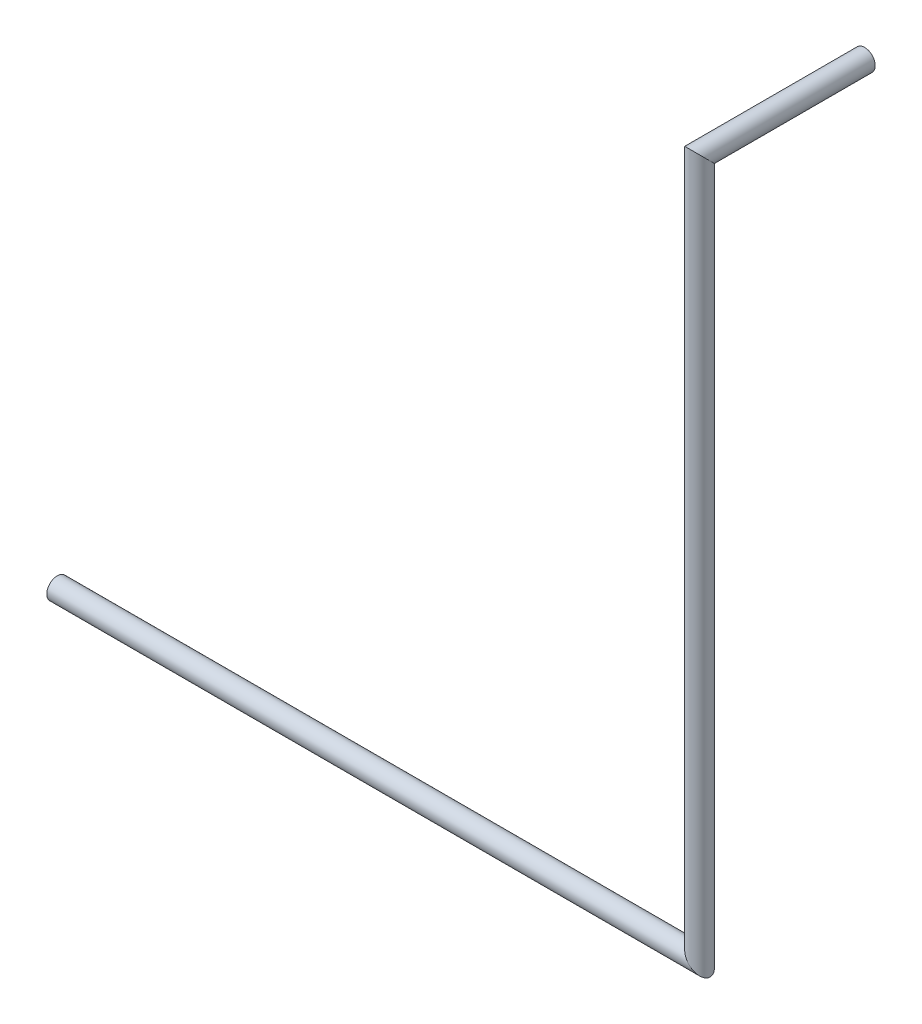
SolidWorks part; units mm, degrees
ref_plane "Plan de face" through (0, 0, 0) normal (0, 0, 1) x (1, 0, 0)
ref_plane "Plan de dessus" through (0, 0, 0) normal (0, 1, 0) x (1, 0, 0)
ref_plane "Plan de droite" through (0, 0, 0) normal (1, 0, 0) x (0, 0, -1)
sketch3d "Esquisse3D1"
  line L0 (0, 0, 0) -> (152.47, 0, 0)
  line L1 (152.47, 0, 0) -> (152.47, 165.26, 0)
  line L2 (152.47, 165.26, 0) -> (152.47, 165.26, -39.19)
  dimension "D1" = 152.47
  dimension "D2" = 165.26
  dimension "D3" = 39.19
sketch "Esquisse1" plane through (0, 0, 0) normal (1, 0, 0) x (0, 0, -1)
  circle A0 centre (0, 0) radius 2.5
  dimension "D1" = 5
sweep "Balayage1" add profiles "Esquisse1" path "Esquisse3D1"
